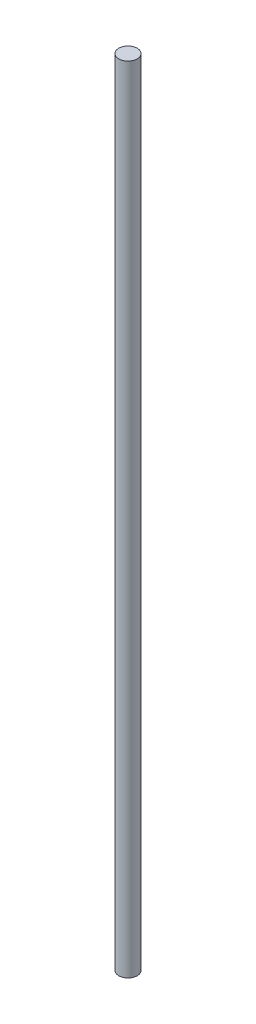
SolidWorks part; units mm, degrees
ref_plane "Alzado" through (0, 0, 0) normal (0, 0, 1) x (1, 0, 0)
ref_plane "Planta" through (0, 0, 0) normal (0, 1, 0) x (1, 0, 0)
ref_plane "Vista lateral" through (0, 0, 0) normal (1, 0, 0) x (0, 0, -1)
sketch "Croquis1" plane through (0, 0, 0) normal (0, 1, 0) x (1, 0, 0)
  circle A0 centre (0, 0) radius 4
extrude "Saliente-Extruir1" add sketch "Croquis1" along normal blind 344
